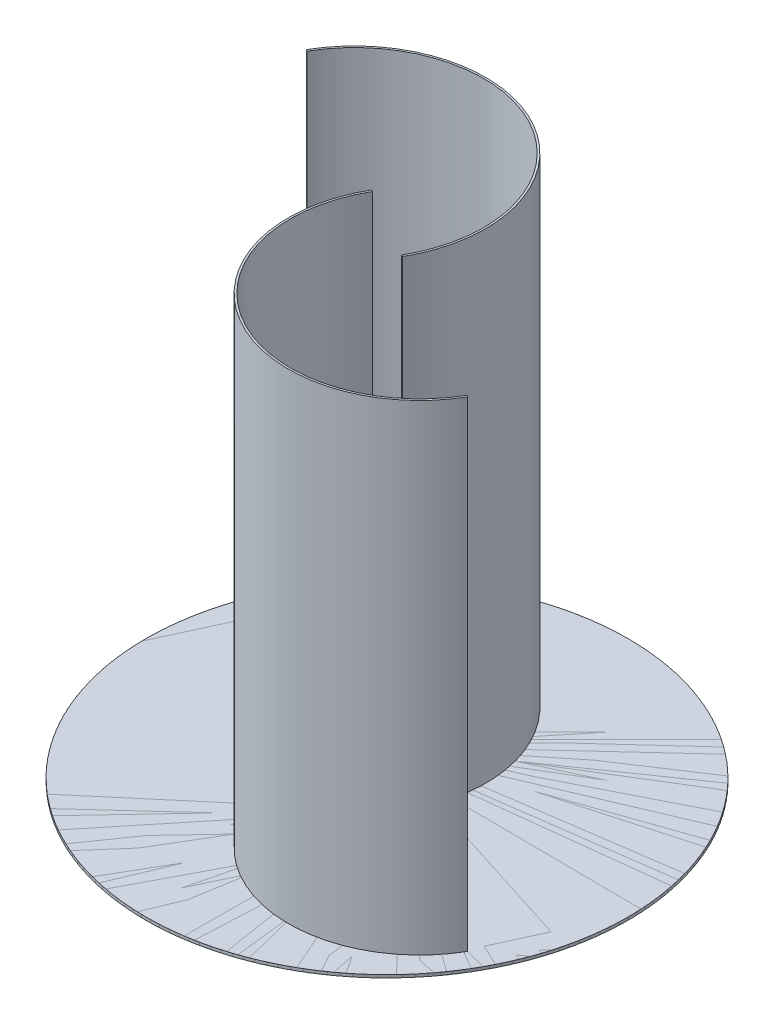
SolidWorks part; units mm, degrees
ref_plane "Alzado" through (0, 0, 0) normal (0, 0, 1) x (1, 0, 0)
ref_plane "Planta" through (0, 0, 0) normal (0, 1, 0) x (1, 0, 0)
ref_plane "Vista lateral" through (0, 0, 0) normal (1, 0, 0) x (0, 0, -1)
sketch "Croquis1" plane through (0, 0, 0) normal (0, 1, 0) x (1, 0, 0)
  circle A0 centre (0, 0) radius 250
  dimension "De" = 500
extrude "Saliente-Extruir1" add sketch "Croquis1" along normal blind 3
sketch "Croquis2" plane through (0, 3, 0) normal (0, 1, 0) x (1, 0, 0)
  line L0 (-250, 0) -> (250, 0) construction
  line L5 (-216.5064, 125) -> (216.5064, -125) construction
  line L6 (-197.69, 114.1364) -> (-195.9579, 113.1364)
  line L7 (36.1369, -20.8636) -> (37.8689, -21.8636)
  arc A0 (-196.824, 113.6364) -> (37.0029, -21.3636) centre (-79.9105, 46.1364) cw construction
  circle A8 centre (0, 0) radius 250 construction
  arc A9 (-197.69, 114.1364) -> (37.8689, -21.8636) centre (-79.9105, 46.1364) cw
  arc A10 (-195.9579, 113.1364) -> (36.1369, -20.8636) centre (-79.9105, 46.1364) cw
  circle A11 centre (0, 0) radius 227.2727 construction
  dimension "D2" = 454.5455
  dimension "d" = 135
  dimension "D1" = 30
  dimension "D4" = 2
  dimension "e" = 42.7273
extrude "Saliente-Extruir2" add sketch "Croquis2" along normal blind 498
pattern_circular "MatrizC1" count 2 over 360 about axis through (0, 0, 0) along (0, 1, 0) of bodies 102
equation "\"D2@Croquis2\"=\"De@Croquis1\"/1.1"
